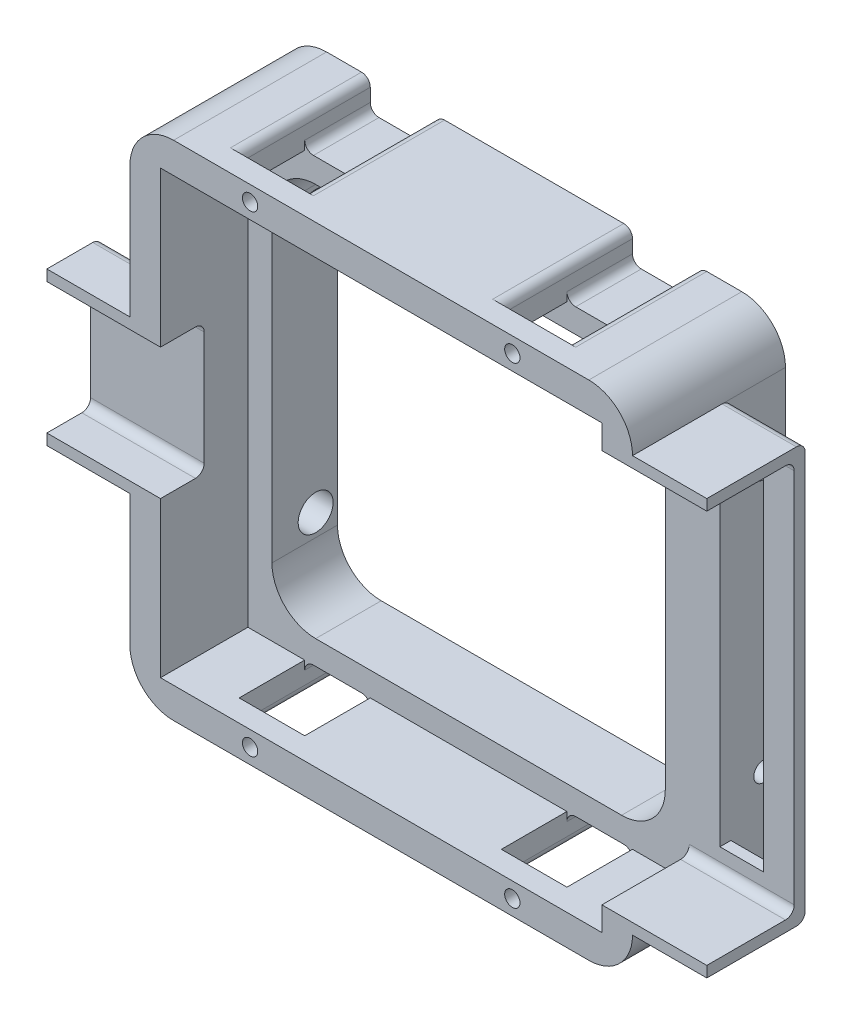
SolidWorks part; units mm, degrees
ref_plane "Front Plane" through (0, 0, 0) normal (0, 0, 1) x (1, 0, 0)
ref_plane "Top Plane" through (0, 0, 0) normal (0, 1, 0) x (1, 0, 0)
ref_plane "Right Plane" through (0, 0, 0) normal (1, 0, 0) x (0, 0, -1)
sketch "Sketch1" plane through (0, 0, 0) normal (0, 0, 1) x (1, 0, 0)
  line L1 (57.5, -57.5) -> (-57.5, -57.5)
  line L2 (57.5, -57.5) -> (57.5, 57.5)
  line L3 (57.5, 57.5) -> (-57.5, 57.5)
  line L4 (-57.5, -57.5) -> (-57.5, 57.5)
  line L5 (57.5, -57.5) -> (-57.5, 57.5) construction
  line L6 (57.5, 57.5) -> (-57.5, -57.5) construction
  point P0 (0, 0)
  dimension "D1" = 115
  dimension "D2" = 115
extrude "Boss-Extrude1" add sketch "Sketch1" along normal mid plane 60
fillet "Fillet1" radius 10 4 edges at (-57.5, -57.5, 0) (57.5, -57.5, 0) (57.5, 57.5, 0) (-57.5, 57.5, 0)
ref_plane "Plane1" through (0, 0, 30) normal (0, 0, 1) x (1, 0, 0)
sketch "Sketch4" plane through (0, 0, 30) normal (0, 0, 1) x (1, 0, 0)
  line L1 (50.5, -50.5) -> (-50.5, -50.5)
  line L2 (50.5, -50.5) -> (50.5, 50.5)
  line L3 (50.5, 50.5) -> (-50.5, 50.5)
  line L4 (-50.5, -50.5) -> (-50.5, 50.5)
  line L5 (50.5, -50.5) -> (-50.5, 50.5) construction
  line L6 (50.5, 50.5) -> (-50.5, -50.5) construction
  point P0 (0, 0)
  dimension "D1" = 101
  dimension "D2" = 101
extrude "Cut-Extrude3" cut sketch "Sketch4" against normal blind 20
ref_plane "Plane2" through (0, 0, -30) normal (0, 0, -1) x (-1, 0, 0)
ref_plane "Plane3" through (0, 0, 10) normal (0, 0, 1) x (1, 0, 0)
sketch "Sketch7" plane through (0, 0, 10) normal (0, 0, 1) x (1, 0, 0)
  line L1 (45, -45) -> (-45, -45)
  line L2 (45, -45) -> (45, 45)
  line L3 (45, 45) -> (-45, 45)
  line L4 (-45, -45) -> (-45, 45)
  line L5 (45, -45) -> (-45, 45) construction
  line L6 (45, 45) -> (-45, -45) construction
  point P0 (0, 0)
  dimension "D1" = 90
  dimension "D2" = 90
extrude "Cut-Extrude5" cut sketch "Sketch7" against normal blind 60
fillet "Fillet3" radius 10 4 edges at (-45, -45, -10) (45, -45, -10) (-45, 45, -10) (45, 45, -10)
sketch "Sketch8" plane through (0, 0, -30) normal (0, 0, -1) x (-1, 0, 0)
  circle A0 centre (-48, 48) radius 3.15
  dimension "D1" = 6.3
  dimension "D2" = 48
  dimension "D3" = 48
extrude "Cut-Extrude6" cut sketch "Sketch8" against normal blind 35
mirror "Mirror2" about plane through (0, 0, 0) normal (0, 1, 0) of "Cut-Extrude6" second plane through (0, 0, 0) second plane normal (1, 0, 0)
sketch "Sketch9" plane through (0, 0, 10) normal (0, 0, 1) x (1, 0, 0)
  circle A0 centre (-48, 48) radius 1.25
  dimension "D1" = 2.5
  dimension "D2" = 48
  dimension "D3" = 48
extrude "Cut-Extrude7" [suppressed] cut sketch "Sketch9" against normal blind 15
mirror "Mirror3" [suppressed] about plane through (0, 0, 0) normal (0, 1, 0)
sketch "Sketch10" [suppressed] plane through (0, 0, -5) normal (0, 0, 1) x (1, 0, 0)
  circle A0 centre (-48, 48) radius 2.5
  dimension "D1" = 5
extrude "Cut-Extrude8" [suppressed] cut sketch "Sketch10" against normal blind 3
mirror "Mirror4" [suppressed] about plane through (0, 0, 0) normal (0, 1, 0)
ref_plane "Plane4" through (57.5, 0, 0) normal (1, 0, 0) x (0, 0, -1)
sketch "Sketch11" plane through (57.5, 0, 0) normal (1, 0, 0) x (0, 0, -1)
  line L0 (-30, 23.375) -> (-30, -23.375) construction
  line L1 (-50, -45) -> (-10, -45)
  line L2 (-50, -45) -> (-50, 45)
  line L3 (-50, 45) -> (-10, 45)
  line L4 (-10, -45) -> (-10, 45)
  line L5 (-50, -45) -> (-10, 45) construction
  line L6 (-50, 45) -> (-10, -45) construction
  point P0 (-30, 0)
  dimension "D1" = 90
  dimension "D2" = 40
extrude "Cut-Extrude9" cut sketch "Sketch11" against normal blind 11
sketch "Sketch13" plane through (57.5, 0, 0) normal (1, 0, 0) x (0, 0, -1)
  line L0 (-30, 23.375) -> (-30, -23.375) construction
  line L1 (-10, 45) -> (-7.5, 45)
  line L2 (-10, 45) -> (-10, -45)
  line L3 (-10, -45) -> (-7.5, -45)
  line L4 (-7.5, 45) -> (-7.5, -45)
  line L5 (-7.5, 45) -> (-30, 45)
  line L6 (-7.5, 45) -> (-7.5, 47.5)
  line L7 (-7.5, 47.5) -> (-30, 47.5)
  line L8 (-30, 45) -> (-30, 47.5)
  line L9 (30, 47.5) -> (-30, 47.5) construction
  line L10 (-30, -47.5) -> (30, -47.5) construction
  line L11 (-7.5, -45) -> (-30, -45)
  line L12 (-7.5, -45) -> (-7.5, -47.5)
  line L13 (-7.5, -47.5) -> (-30, -47.5)
  line L14 (-30, -45) -> (-30, -47.5)
  dimension "D1" = 90
  dimension "D2" = 2.5
extrude "Boss-Extrude2" add sketch "Sketch13" along normal blind 17 contours L4 L1 L2 L3 | L11 L14 L13 L12 L3 | L8 L5 L1 L6 L7
fillet "Fillet6" radius 2 4 edges at (62.5, -45, 10) (66, -47.5, 7.5) (62.5, 45, 10) (66, 47.5, 7.5)
ref_plane "Plane5" through (-57.5, 0, 0) normal (-1, 0, 0) x (0, 0, 1)
sketch "Sketch14" plane through (-57.5, 0, 0) normal (-1, 0, 0) x (0, 0, 1)
  line L0 (30, 47.5) -> (30, -47.5) construction
  line L1 (40, -15) -> (20, -15)
  line L2 (40, -15) -> (40, 15)
  line L3 (40, 15) -> (20, 15)
  line L4 (20, -15) -> (20, 15)
  line L5 (40, -15) -> (20, 15) construction
  line L6 (40, 15) -> (20, -15) construction
  point P0 (30, 0)
  dimension "D1" = 30
  dimension "D2" = 20
extrude "Cut-Extrude10" cut sketch "Sketch14" against normal blind 11
sketch "Sketch15" plane through (-57.5, 0, 0) normal (-1, 0, 0) x (0, 0, 1)
  line L0 (30, -23.375) -> (30, 23.375) construction
  line L1 (20, 15) -> (30, 15)
  line L2 (20, 15) -> (20, 17.5)
  line L3 (20, 17.5) -> (30, 17.5)
  line L4 (30, 15) -> (30, 17.5)
  line L5 (30, -15) -> (30, -47.5) construction
  line L6 (20, -15) -> (30, -15)
  line L7 (20, -15) -> (20, -17.5)
  line L8 (20, -17.5) -> (30, -17.5)
  line L9 (30, -15) -> (30, -17.5)
  line L11 (20, 17.5) -> (17.5, 17.5)
  line L12 (20, 17.5) -> (20, -17.5)
  line L13 (20, -17.5) -> (17.5, -17.5)
  line L14 (17.5, 17.5) -> (17.5, -17.5)
  dimension "D1" = 2.5
  dimension "D2" = 2.5
  dimension "D3" = 2.5
extrude "Boss-Extrude3" add sketch "Sketch15" along normal blind 19 contours L11 L14 L13 L7 L12 L2 | L1 L4 L3 L2 | L9 L6 L7 L8
fillet "Fillet7" radius 2 4 edges at (-63.5, -15, 20) (-63.5, 15, 20) (-67, -17.5, 17.5) (-67, 17.5, 17.5)
ref_plane "Plane6" through (0, 0, -30) normal (0, 0, -1) x (-1, 0, 0)
sketch "Sketch16" plane through (0, 0, -30) normal (0, 0, -1) x (-1, 0, 0)
  line L0 (-57.5, 31.35) -> (-57.5, -31.35) construction
  line L1 (57.5, -57.5) -> (-57.5, -57.5)
  line L2 (57.5, -57.5) -> (57.5, 57.5)
  line L3 (57.5, 57.5) -> (-57.5, 57.5)
  line L4 (-57.5, -57.5) -> (-57.5, 57.5)
  line L5 (57.5, -57.5) -> (-57.5, 57.5) construction
  line L6 (57.5, 57.5) -> (-57.5, -57.5) construction
  point P0 (0, 0)
  dimension "D1" = 115
extrude "Cut-Extrude12" cut sketch "Sketch16" against normal blind 25
ref_plane "Plane7" through (0, 0, 7.5) normal (0, 0, -1) x (-1, 0, 0)
sketch "Sketch17" plane through (0, 0, 7.5) normal (0, 0, -1) x (-1, 0, 0)
  line L1 (-57.5, -40) -> (-67.5, -40)
  line L2 (-57.5, -40) -> (-57.5, 40)
  line L3 (-57.5, 40) -> (-67.5, 40)
  line L4 (-67.5, -40) -> (-67.5, 40)
  line L5 (-57.5, -40) -> (-67.5, 40) construction
  line L6 (-57.5, 40) -> (-67.5, -40) construction
  point P0 (-62.5, 0)
  dimension "D1" = 62.5
  dimension "D2" = 10
  dimension "D3" = 80
extrude "Cut-Extrude13" cut sketch "Sketch17" against normal blind 15
sketch "Sketch20" plane through (57.5, 0, 0) normal (1, 0, 0) x (0, 0, -1)
  circle A1 centre (0, 30) radius 2.25
  dimension "D1" = 4.5
  dimension "D2" = 30
  dimension "D3" = 0
extrude "Cut-Extrude14" cut sketch "Sketch20" against normal blind 25
mirror "Mirror8" about plane through (0, 0, 0) normal (1, 0, 0) of "Cut-Extrude14" second plane through (0, 0, 0) second plane normal (0, 1, 0)
sketch "Sketch21" plane through (0, 0, 30) normal (0, 0, 1) x (1, 0, 0)
  circle A1 centre (30, 54) radius 1.75
  dimension "D1" = 3.5
  dimension "D2" = 30
  dimension "D3" = 54
extrude "Cut-Extrude15" cut sketch "Sketch21" against normal blind 20
mirror "Mirror9" about plane through (0, 0, 0) normal (0, 1, 0) of "Cut-Extrude15" second plane through (0, 0, 0) second plane normal (1, 0, 0)
ref_plane "Plane8" through (0, 57.5, 0) normal (0, 1, 0) x (1, 0, 0)
sketch "Sketch24" plane through (0, 57.5, 0) normal (0, 1, 0) x (1, 0, 0)
  line L5 (22.5, 0) -> (37.5, 0)
  line L6 (22.5, 0) -> (22.5, -25)
  line L7 (22.5, -25) -> (37.5, -25)
  line L8 (37.5, 0) -> (37.5, -25)
  line L9 (22.5, 0) -> (37.5, -25) construction
  line L10 (22.5, -25) -> (37.5, 0) construction
  point P0 (30, -12.5)
  dimension "D1" = 25
  dimension "D2" = 30
  dimension "D3" = 12.5
  dimension "D4" = 15
extrude "Cut-Extrude16" cut sketch "Sketch24" against normal blind 7
mirror "Mirror10" about plane through (0, 0, 0) normal (1, 0, 0) of "Cut-Extrude16" second plane through (0, 0, 0) second plane normal (0, 1, 0)
ref_plane "Plane9" through (45, 0, 0) normal (-1, 0, 0) x (0, 0, 1)
sketch "Sketch25" plane through (45, 0, 0) normal (-1, 0, 0) x (0, 0, 1)
  circle A0 centre (0, 30) radius 4
  point P4 (0, 0)
  dimension "D1" = 8
  dimension "D2" = 0
extrude "Cut-Extrude17" cut sketch "Sketch25" against normal blind 7.5
mirror "Mirror11" about plane through (0, 0, 0) normal (0, 1, 0) of "Cut-Extrude17" second plane through (0, 0, 0) second plane normal (1, 0, 0)
ref_plane "Plane10" through (0, 0, 5) normal (0, 0, 1) x (1, 0, 0)
sketch "Sketch26" plane through (0, 0, 5) normal (0, 0, 1) x (1, 0, 0)
  line L0 (-35, 45) -> (-35, 50.5)
  line L1 (50.5, 50.5) -> (37.5, 50.5) construction
  line L2 (-35, 50.5) -> (-50.5, 50.5)
  line L3 (-50.5, 50.5) -> (-50.5, 35)
  line L4 (-50.5, 50.5) -> (-50.5, 15) construction
  line L5 (-50.5, 35) -> (-45, 35)
  arc A0 (-45, 35) -> (-35, 45) centre (-35, 35) cw
extrude "Cut-Extrude18" [suppressed] cut sketch "Sketch26" against normal blind 5
ref_plane "Plane11" through (0, 0, -5) normal (0, 0, -1) x (-1, 0, 0)
sketch "Sketch28" plane through (0, 0, -5) normal (0, 0, -1) x (-1, 0, 0)
  line L1 (-37.5, 64.5) -> (-22.5, 64.5)
  line L2 (-37.5, 64.5) -> (-37.5, 50.5)
  line L3 (-37.5, 50.5) -> (-22.5, 50.5)
  line L4 (-22.5, 64.5) -> (-22.5, 50.5)
  line L5 (-37.5, 64.5) -> (-22.5, 50.5) construction
  line L6 (-37.5, 50.5) -> (-22.5, 64.5) construction
  point P0 (-30, 57.5)
  dimension "D3" = 14
  dimension "D1" = 30
  dimension "D2" = 57.5
  dimension "D4" = 15
extrude "Cut-Extrude20" cut sketch "Sketch28" against normal blind 20
mirror "Mirror12" about plane through (0, 0, 0) normal (0, 1, 0) of "Cut-Extrude20" second plane through (0, 0, 0) second plane normal (1, 0, 0)
fillet "Fillet8" radius 2 16 edges at (37.5, 50.5, 2.5) (22.5, 50.5, 2.5) (37.5, 57.5, 10) (22.5, 57.5, 10) (37.5, -57.5, 10) (22.5, -57.5, 10) (22.5, -50.5, 2.5) (37.5, -50.5, 2.5) (-37.5, 57.5, 10) (-22.5, 57.5, 10) (-22.5, 50.5, 2.5) (-37.5, 50.5, 2.5) (-37.5, -50.5, 2.5) (-22.5, -50.5, 2.5) (-37.5, -57.5, 10) (-22.5, -57.5, 10)
